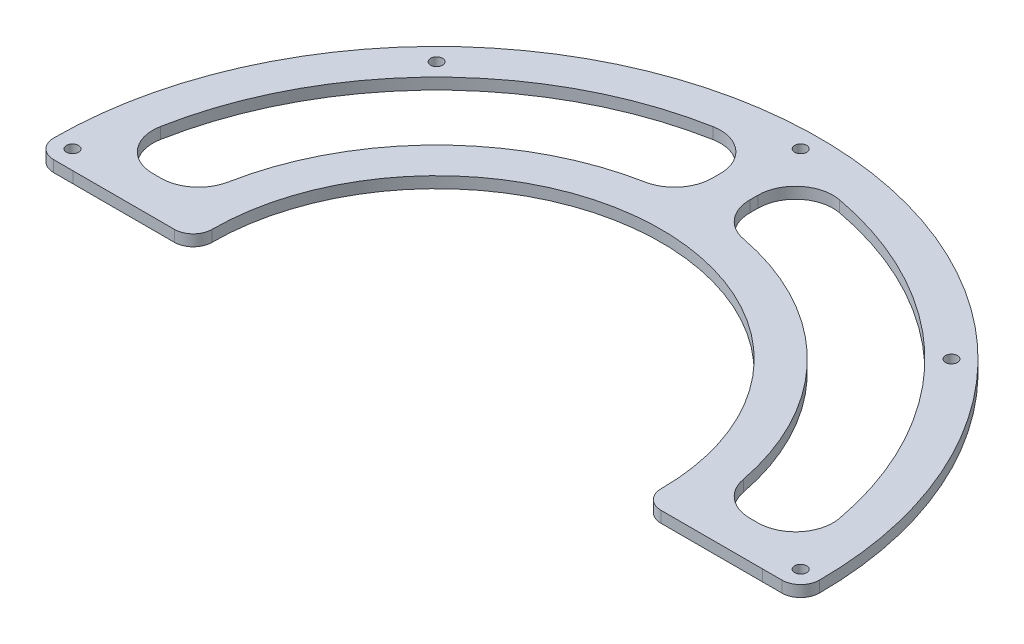
SolidWorks part; units mm, degrees
ref_plane "前视基准面" through (0, 0, 0) normal (0, 0, 1) x (1, 0, 0)
ref_plane "上视基准面" through (0, 0, 0) normal (0, 1, 0) x (1, 0, 0)
ref_plane "右视基准面" through (0, 0, 0) normal (1, 0, 0) x (0, 0, -1)
other "Configuration Table"
sketch "草图1" plane through (0, 0, 0) normal (0, 1, 0) x (1, 0, 0)
  line L0 (-80.5147, 5) -> (-78.347, 5)
  line L1 (-64.5767, -5) -> (-59.5605, -5)
  line L9 (64.5767, -5) -> (59.5605, -5)
  line L18 (-91.7639, -5) -> (-64.5767, -5)
  line L24 (-91.7896, 4.5039) -> (-64.6922, 3.1743) construction
  line L25 (101.7776, 4.994) -> (64.6922, 3.1743) construction
  line L26 (4.994, 101.7776) -> (3.1743, 64.6922) construction
  line L28 (5, 80.5147) -> (5, 78.347)
  line L30 (-5, 80.5147) -> (-5, 78.347)
  line L32 (78.347, 5) -> (80.5147, 5)
  line L37 (64.5767, -5) -> (91.7639, -5)
  line L39 (5, -101.9) -> (4.994, -101.7776) construction
  line L43 (-62.458, 80.5147) -> (-56.3286, 72.6133) construction
  line L45 (-101.7776, -4.994) -> (-91.7639, -5)
  line L46 (91.7639, -5) -> (101.7776, -4.994)
  line L47 (-64.6922, -3.1743) -> (-101.7776, -4.994) construction
  line L49 (-3.1743, 64.6922) -> (-4.994, 101.7776) construction
  line L50 (0, 64.77) -> (0, 96.9) construction
  line L53 (64.6922, -3.1743) -> (101.7776, -4.994) construction
  arc A27 (68.5254, 13.1196) -> (13.1196, 68.5254) centre (0, 0) ccw
  arc A28 (64.5767, -5) -> (-64.6922, 3.1743) centre (0, 0) ccw construction
  arc A29 (90.3455, 16.8315) -> (16.8315, 90.3455) centre (0, 0) ccw
  arc A30 (88.7593, -5) -> (-88.7932, 4.3569) centre (0, 0) ccw construction
  arc A31 (-16.8315, 90.3455) -> (-90.3455, 16.8315) centre (0, 0) ccw
  arc A33 (101.7776, -4.994) -> (-101.7776, -4.994) centre (0, 0) ccw
  arc A34 (-88.7932, -4.3569) -> (-88.7593, -5) centre (0, 0) ccw construction
  arc A36 (-64.6922, -3.1743) -> (-64.5767, -5) centre (0, 0) ccw construction
  arc A37 (-13.1196, 68.5254) -> (-68.5254, 13.1196) centre (0, 0) ccw
  arc A41 (80.5147, 5) -> (90.3455, 16.8315) centre (80.5147, 15) ccw
  arc A42 (78.347, 5) -> (68.5254, 13.1196) centre (78.347, 15) cw
  arc A43 (5, 78.347) -> (13.1196, 68.5254) centre (15, 78.347) ccw
  arc A44 (16.8315, 90.3455) -> (5, 80.5147) centre (15, 80.5147) ccw
  arc A45 (-68.5254, 13.1196) -> (-78.347, 5) centre (-78.347, 15) cw
  arc A46 (-5, 78.347) -> (-13.1196, 68.5254) centre (-15, 78.347) cw
  arc A47 (-5, 80.5147) -> (-16.8315, 90.3455) centre (-15, 80.5147) ccw
  arc A48 (-80.5147, 5) -> (-90.3455, 16.8315) centre (-80.5147, 15) cw
  circle A61 centre (0, 0) radius 96.9 construction
  circle A62 centre (0, 96.9) radius 1.6
  circle A63 centre (68.5186, 68.5186) radius 1.6
  circle A64 centre (96.9, 0) radius 1.6
  circle A68 centre (-96.9, 0) radius 1.6
  circle A69 centre (-68.5186, 68.5186) radius 1.6
  circle A70 centre (68.5186, -68.5186) radius 1.6 [skipped]
  circle A71 centre (0, -96.9) radius 1.6 [skipped]
  circle A72 centre (-68.5186, -68.5186) radius 1.6 [skipped]
  arc A75 (90.3455, 16.8315) -> (-90.3455, 16.8315) centre (0, 0) ccw
  arc A76 (59.5605, -5) -> (-59.5605, -5) centre (0, 0) ccw
  point P83 (91.7639, 5)
  point P86 (69.5906, 5)
  point P97 (-5, 91.7639)
  point P111 (59.5605, 5)
  point P116 (-5, 59.5605)
  point P119 (-59.5605, 5)
  point P131 (-59.3933, 76.564)
  dimension "D2" = 10
  dimension "D9" = 3.2
  dimension "D10" = 2
  dimension "D11" = 8
extrude "凸台-拉伸1" add sketch "草图1" along normal blind 3
fillet "圆角1" radius 5 2 edges at (101.7776, 1.5, 4.994) (-101.7776, 1.5, 4.994)
fillet "圆角2" radius 5 2 edges at (59.5605, 1.5, 5) (-59.5605, 1.5, 5)
